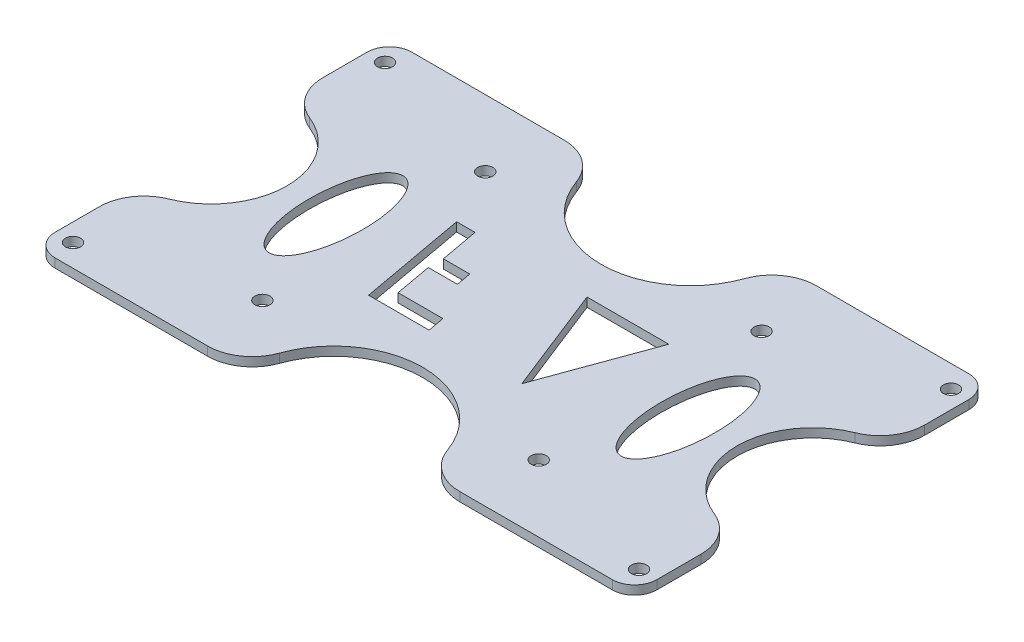
SolidWorks part; units mm, degrees
ref_plane "前视" through (0, 0, 0) normal (0, 0, 1) x (1, 0, 0)
ref_plane "上视" through (0, 0, 0) normal (0, 1, 0) x (1, 0, 0)
ref_plane "右视" through (0, 0, 0) normal (1, 0, 0) x (0, 0, -1)
sketch "草图1" plane through (0, 0, 0) normal (0, 1, 0) x (1, 0, 0)
  line L0 (-10.5, -40) -> (25.5, -40)
  line L1 (-67.5, -40) -> (-10.5, -40)
  line L2 (-67.5, -40) -> (-67.5, -20)
  line L3 (-67.5, 40) -> (-10.5, 40)
  line L4 (67.5, -40) -> (67.5, -20)
  line L5 (-67.5, -40) -> (67.5, 40) construction
  line L6 (-67.5, 40) -> (67.5, -40) construction
  line L7 (-67.5, 20) -> (-67.5, -20)
  line L8 (-10.5, 40) -> (25.5, 40)
  line L9 (67.5, 20) -> (67.5, -20)
  line L14 (-67.5, 20) -> (-67.5, 40)
  line L15 (67.5, 20) -> (67.5, 40)
  line L16 (25.5, 40) -> (67.5, 40)
  line L17 (25.5, -40) -> (67.5, -40)
  point P0 (0, 0)
  point P5 (0, 0)
  dimension "D1" = 135
  dimension "D2" = 80
extrude "凸台-拉伸1" add sketch "草图1" along normal blind 2
sketch "草图2" plane through (0, 2, 0) normal (0, 1, 0) x (1, 0, 0)
  line L0 (67.5, 40) -> (-67.5, 40) construction
  line L1 (-67.5, 40) -> (-67.5, -40) construction
  line L2 (0, 33.1346) -> (0, -39.2456) construction
  line L3 (-56, 0) -> (46.6474, 0) construction
  circle A0 centre (-63.5, 35) radius 1.7
  circle A1 centre (63.5, 35) radius 1.7
  circle A2 centre (63.5, -35) radius 1.7
  circle A3 centre (-63.5, -35) radius 1.7
  dimension "D1" = 5
  dimension "D2" = 4
  dimension "D3" = 3.4
extrude "切除-拉伸1" cut sketch "草图2" against normal blind 2
sketch "草图3" plane through (0, 2, 0) normal (0, 1, 0) x (1, 0, 0)
  line L1 (-31, -25) -> (31, -25) construction
  line L2 (-31, -25) -> (-31, 25) construction
  line L3 (-31, 25) -> (31, 25) construction
  line L4 (31, -25) -> (31, 25) construction
  line L5 (-31, -25) -> (31, 25) construction
  line L6 (-31, 25) -> (31, -25) construction
  circle A0 centre (-31, 25) radius 1.7
  circle A1 centre (31, 25) radius 1.7
  circle A2 centre (-31, -25) radius 1.7
  circle A3 centre (31, -25) radius 1.7
  point P0 (0, 0)
  dimension "D1" = 62
  dimension "D2" = 50
  dimension "D3" = 0
extrude "切除-拉伸2" cut sketch "草图3" against normal blind 3
sketch "草图4" plane through (0, 2, 0) normal (0, 1, 0) x (1, 0, 0)
  line L0 (67.5, 40) -> (-67.5, 40) construction
  line L1 (-67.5, 40) -> (-67.5, -40) construction
  line L2 (0, 47.2554) -> (0, -18.354) construction
  line L3 (-18.0883, 0) -> (21.7232, 0) construction
  line L4 (-67.5, 17) -> (-67.5, -17)
  line L5 (67.5, 17) -> (67.5, -17)
  line L6 (-20, 40) -> (20, 40)
  line L7 (-20, -40) -> (20, -40)
  arc A0 (-20, 40) -> (20, 40) centre (0, 40) ccw
  arc A1 (-67.5, -17) -> (-67.5, 17) centre (-67.5, 0) ccw
  arc A2 (67.5, -17) -> (67.5, 17) centre (67.5, 0) cw
  arc A3 (-20, -40) -> (20, -40) centre (0, -40) cw
  ellipse E0 centre (-39.5, 0) end of major axis (-39.5, -15) minor radius 6
  ellipse E1 centre (39.5, 0) end of major axis (39.5, -15) minor radius 6
  dimension "D1" = 40
  dimension "D2" = 34
  dimension "D3" = 28
extrude "切除-拉伸3" cut sketch "草图4" against normal blind 3
fillet "圆角1" radius 5 4 edges at (67.5, 1, -40) (67.5, 1, 40) (-67.5, 1, 40) (-67.5, 1, -40)
fillet "圆角2" radius 10 7 edges at (20, 1, 40) (-20, 1, 40) (-20, 1, -40) (-67.5, 1, 17) (-67.5, 1, -17) (67.5, 1, -17) (67.5, 1, 17)
sketch "草图6" plane through (0, 0, 0) normal (0, -1, 0) x (1, 0, 0)
  line L0 (-24.5054, -12.0764) -> (-20.098, 12.0764)
  line L1 (-20.098, 12.0764) -> (-6.523, 12.0764)
  line L2 (-6.523, 12.0764) -> (-7.2166, 8.2755)
  line L3 (-7.2166, 8.2755) -> (-17.2772, 8.2755)
  line L4 (-17.2772, 8.2755) -> (-18.7873, 0)
  line L5 (-18.7873, 0) -> (-12.2469, 0)
  line L6 (-12.2469, 0) -> (-12.8657, -3.3909)
  line L7 (-12.8657, -3.3909) -> (-18.7873, -3.3909)
  line L8 (-18.7873, -3.3909) -> (-20.3723, -12.0764)
  line L9 (-20.3723, -12.0764) -> (-24.5054, -12.0764)
  line L10 (14.2801, 12.0764) -> (4.76, -12.0764)
  line L11 (4.76, -12.0764) -> (23.095, -12.0764)
  line L12 (23.095, -12.0764) -> (14.2801, 12.0764)
extrude "切除-拉伸5" cut sketch "草图6" against normal blind 3
